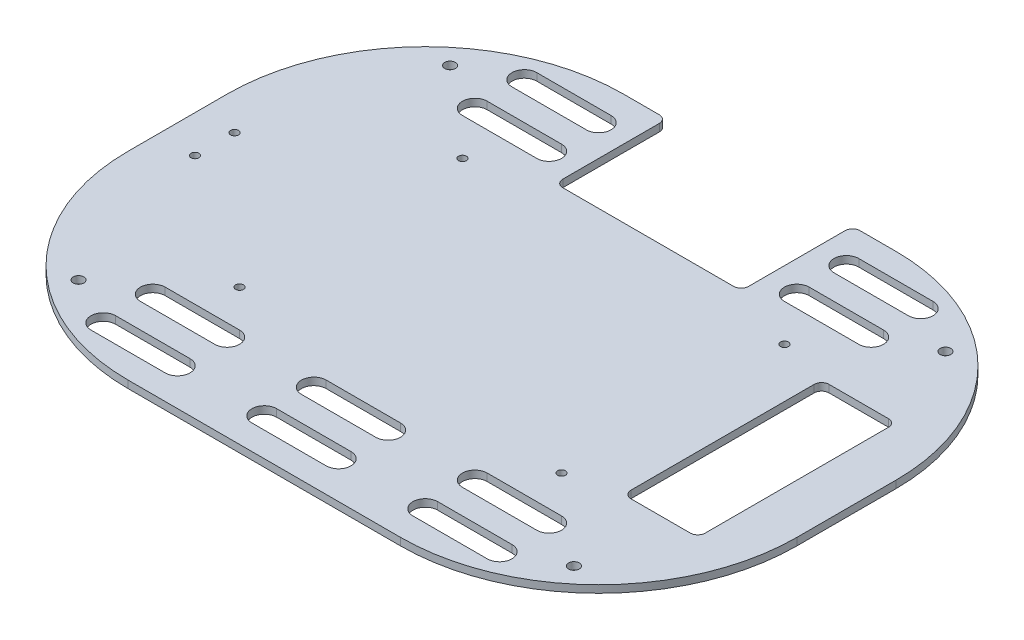
SolidWorks part; units mm, degrees
ref_plane "前视基准面" through (0, 0, 0) normal (0, 0, 1) x (1, 0, 0)
ref_plane "上视基准面" through (0, 0, 0) normal (0, 1, 0) x (1, 0, 0)
ref_plane "右视基准面" through (0, 0, 0) normal (1, 0, 0) x (0, 0, -1)
other "Configuration Table"
sketch "草图1" plane through (0, 0, 0) normal (0, 1, 0) x (1, 0, 0)
  line L1 (-135, -100) -> (135, -100)
  line L2 (-135, -100) -> (-135, 100)
  line L3 (-135, 100) -> (135, 100)
  line L4 (135, -100) -> (135, 100)
  line L5 (-135, -100) -> (135, 100) construction
  line L6 (-135, 100) -> (135, -100) construction
  point P0 (0, 0)
  dimension "D1" = 200
  dimension "D2" = 270
extrude "凸台-拉伸1" add sketch "草图1" along normal blind 3
sketch "草图2" plane through (0, 3, 0) normal (0, 1, 0) x (1, 0, 0)
  line L1 (100, -75) -> (-100, -75) construction
  line L2 (100, -75) -> (100, 75) construction
  line L3 (100, 75) -> (-100, 75) construction
  line L4 (-100, -75) -> (-100, 75) construction
  line L5 (100, -75) -> (-100, 75) construction
  line L6 (100, 75) -> (-100, -75) construction
  circle A0 centre (-100, 75) radius 2.15
  circle A1 centre (100, 75) radius 2.15
  circle A2 centre (100, -75) radius 2.15
  circle A3 centre (-100, -75) radius 2.15
  point P0 (0, 0)
  dimension "D3" = 4.3
  dimension "D1" = 150
  dimension "D2" = 200
extrude "切除-拉伸1" cut sketch "草图2" against normal blind 3
sketch "草图3" plane through (0, 3, 0) normal (0, 1, 0) x (1, 0, 0)
  line L0 (0, 0) -> (-135, 0) construction
  line L1 (-135, 100) -> (-135, -100) construction
  circle A0 centre (-120, 8) radius 1.6
  circle A1 centre (-120, -8) radius 1.6
  dimension "D2" = 3.2
  dimension "D1" = 16
  dimension "D3" = 15
extrude "切除-拉伸2" cut sketch "草图3" against normal blind 3
sketch "草图4" plane through (0, 3, 0) normal (0, 1, 0) x (1, 0, 0)
  line L0 (0, 46.6427) -> (0, 0) construction
  line L1 (0, 0) -> (90.0538, 0) construction
  line L2 (-80, -85) -> (-50, -85) construction
  line L3 (-80, -80) -> (-50, -80)
  line L4 (-80, -90) -> (-50, -90)
  line L5 (-135, -100) -> (135, -100) construction
  line L8 (-15, -85) -> (15, -85) construction
  line L11 (-15, -80) -> (15, -80)
  line L12 (-15, -90) -> (15, -90)
  line L13 (50, -85) -> (80, -85) construction
  line L14 (50, -80) -> (80, -80)
  line L15 (50, -90) -> (80, -90)
  line L16 (-15, -65) -> (15, -65) construction
  line L17 (-15, -60) -> (15, -60)
  line L18 (-15, -70) -> (15, -70)
  line L19 (50, -65) -> (80, -65) construction
  line L20 (50, -60) -> (80, -60)
  line L21 (50, -70) -> (80, -70)
  line L22 (-80, -65) -> (-50, -65) construction
  line L23 (-80, -60) -> (-50, -60)
  line L24 (-80, -70) -> (-50, -70)
  line L25 (-80, 85) -> (-50, 85) construction
  line L26 (-80, 80) -> (-50, 80)
  line L27 (-80, 90) -> (-50, 90)
  line L28 (-15, 85) -> (15, 85) construction
  line L29 (-15, 80) -> (15, 80) construction
  line L30 (-15, 90) -> (15, 90) construction
  line L31 (50, 85) -> (80, 85) construction
  line L32 (50, 80) -> (80, 80)
  line L33 (50, 90) -> (80, 90)
  line L34 (-15, 65) -> (15, 65) construction
  line L35 (-15, 60) -> (15, 60) construction
  line L36 (-15, 70) -> (15, 70) construction
  line L37 (50, 65) -> (80, 65) construction
  line L38 (50, 60) -> (80, 60)
  line L39 (50, 70) -> (80, 70)
  line L40 (-80, 65) -> (-50, 65) construction
  line L41 (-80, 60) -> (-50, 60)
  line L42 (-80, 70) -> (-50, 70)
  line L43 (135, 100) -> (-135, 100) construction
  line L44 (-37.5, 100) -> (37.5, 100)
  line L45 (-37.5, 100) -> (-37.5, 55)
  line L46 (-37.5, 55) -> (37.5, 55)
  line L47 (37.5, 100) -> (37.5, 55)
  arc A0 (-80, -80) -> (-80, -90) centre (-80, -85) ccw
  arc A1 (-50, -90) -> (-50, -80) centre (-50, -85) ccw
  arc A6 (-15, -80) -> (-15, -90) centre (-15, -85) ccw
  arc A7 (15, -90) -> (15, -80) centre (15, -85) ccw
  arc A8 (50, -80) -> (50, -90) centre (50, -85) ccw
  arc A9 (80, -90) -> (80, -80) centre (80, -85) ccw
  arc A10 (-15, -60) -> (-15, -70) centre (-15, -65) ccw
  arc A11 (15, -70) -> (15, -60) centre (15, -65) ccw
  arc A12 (50, -60) -> (50, -70) centre (50, -65) ccw
  arc A13 (80, -70) -> (80, -60) centre (80, -65) ccw
  arc A14 (-80, -60) -> (-80, -70) centre (-80, -65) ccw
  arc A15 (-50, -70) -> (-50, -60) centre (-50, -65) ccw
  arc A16 (-80, 80) -> (-80, 90) centre (-80, 85) cw
  arc A17 (-50, 90) -> (-50, 80) centre (-50, 85) cw
  arc A18 (-15, 80) -> (-15, 90) centre (-15, 85) cw construction
  arc A19 (15, 90) -> (15, 80) centre (15, 85) cw construction
  arc A20 (50, 80) -> (50, 90) centre (50, 85) cw
  arc A21 (80, 90) -> (80, 80) centre (80, 85) cw
  arc A22 (-15, 60) -> (-15, 70) centre (-15, 65) cw construction
  arc A23 (15, 70) -> (15, 60) centre (15, 65) cw construction
  arc A24 (50, 60) -> (50, 70) centre (50, 65) cw
  arc A25 (80, 70) -> (80, 60) centre (80, 65) cw
  arc A26 (-80, 60) -> (-80, 70) centre (-80, 65) cw
  arc A27 (-50, 70) -> (-50, 60) centre (-50, 65) cw
  point P6 (-65, -85)
  point P15 (-65, 85)
  point P18 (0, -85)
  point P25 (65, -85)
  point P32 (0, -65)
  point P39 (65, -65)
  point P46 (-65, -65)
  point P57 (0, 85)
  point P64 (65, 85)
  point P71 (0, 65)
  point P78 (65, 65)
  point P85 (-65, 65)
  dimension "D2" = 5
  dimension "D1" = 30
  dimension "D3" = 65
  dimension "D4" = 15
  dimension "D7" = 20
  dimension "D8" = 75
  dimension "D9" = 35
  dimension "D10" = 45
  dimension "D5" = 3
  dimension "D6" = 2
extrude "切除-拉伸3" cut sketch "草图4" against normal blind 3
sketch "草图5" plane through (0, 3, 0) normal (0, 1, 0) x (1, 0, 0)
  line L1 (-65, 45) -> (65, 45) construction
  line L2 (-65, 45) -> (-65, -45) construction
  line L3 (-65, -45) -> (65, -45) construction
  line L4 (65, 45) -> (65, -45) construction
  line L5 (-65, 45) -> (65, -45) construction
  line L6 (-65, -45) -> (65, 45) construction
  circle A0 centre (-65, -45) radius 1.6
  circle A1 centre (-65, 45) radius 1.6
  circle A2 centre (65, 45) radius 1.6
  circle A3 centre (65, -45) radius 1.6
  point P0 (0, 0)
  dimension "D3" = 3.2
  dimension "D1" = 90
  dimension "D2" = 130
extrude "切除-拉伸4" cut sketch "草图5" against normal blind 3
sketch "草图6" plane through (0, 3, 0) normal (0, 1, 0) x (1, 0, 0)
  line L0 (0, 0) -> (100, 0) construction
  line L2 (85, -40) -> (115, -40)
  line L3 (85, -40) -> (85, 40)
  line L4 (85, 40) -> (115, 40)
  line L5 (115, -40) -> (115, 40)
  line L6 (85, -40) -> (115, 40) construction
  line L7 (85, 40) -> (115, -40) construction
  dimension "D1" = 80
  dimension "D2" = 30
  dimension "D3" = 100
extrude "切除-拉伸5" cut sketch "草图6" against normal blind 3
sketch "草图7" plane through (0, 3, 0) normal (0, 1, 0) x (1, 0, 0)
  line L0 (0, 100) -> (0, 0) construction
  line L1 (135, 100) -> (37.5, 100) construction
  line L2 (0, 0) -> (135, 0) construction
  line L3 (135, -100) -> (135, 100) construction
  line L4 (-135, 100) -> (-135, -100) construction
  line L5 (-55, 100) -> (-135, 100)
  line L6 (-135, 100) -> (-135, 20)
  line L7 (-135, -100) -> (-135, -20)
  line L8 (-55, -100) -> (-135, -100)
  line L9 (55, -100) -> (135, -100)
  line L10 (135, -100) -> (135, -20)
  line L11 (135, 100) -> (135, 20)
  line L12 (55, 100) -> (135, 100)
  arc A0 (-55, 100) -> (-135, 20) centre (-55, 20) ccw
  arc A1 (-55, -100) -> (-135, -20) centre (-55, -20) cw
  arc A2 (55, -100) -> (135, -20) centre (55, -20) ccw
  arc A3 (55, 100) -> (135, 20) centre (55, 20) cw
  dimension "D1" = 80
extrude "切除-拉伸6" cut sketch "草图7" against normal blind 3
fillet "圆角1" radius 3 8 edges at (115, 1.5, 40) (85, 1.5, 40) (115, 1.5, -40) (85, 1.5, -40) (37.5, 1.5, -100) (37.5, 1.5, -55) (-37.5, 1.5, -55) (-37.5, 1.5, -100)
